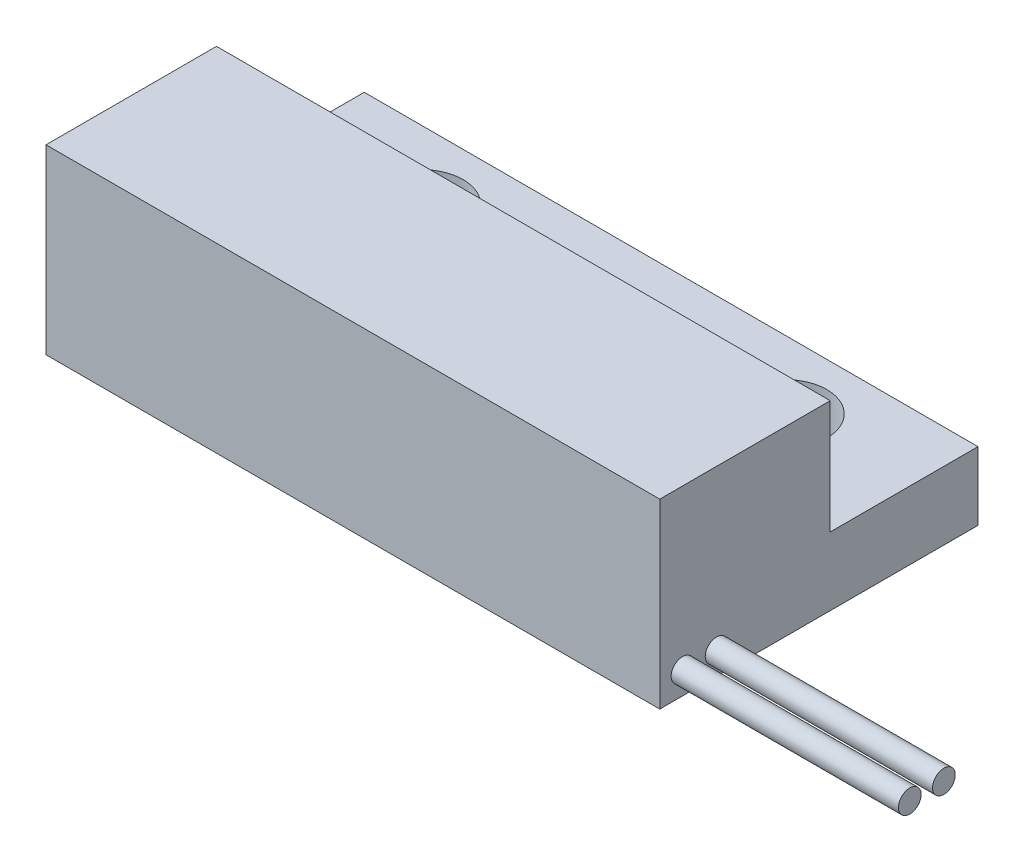
SolidWorks part; units mm, degrees
ref_plane "Alzado" through (0, 0, 0) normal (0, 0, 1) x (1, 0, 0)
ref_plane "Planta" through (0, 0, 0) normal (0, 1, 0) x (1, 0, 0)
ref_plane "Vista lateral" through (0, 0, 0) normal (1, 0, 0) x (0, 0, -1)
sketch "Croquis1" plane through (0, 0, 0) normal (0, 1, 0) x (1, 0, 0)
  line L0 (-13.5, 0) -> (-13.5, -3) construction
  line L1 (0, 0) -> (-27, 0)
  line L2 (0, 0) -> (0, -14)
  line L3 (0, -14) -> (-27, -14)
  line L4 (-27, 0) -> (-27, -14)
  line L5 (-13.5, -3) -> (-21.5, -3) construction
  line L6 (-21.5, -3) -> (-21.5, -14) construction
  line L7 (-21.5, -3) -> (-27, -3) construction
  circle A0 centre (-21.5, -3) radius 1.85
  circle A1 centre (-5.5, -3) radius 1.85
  dimension "D3" = 3.7
  dimension "D1" = 14
  dimension "D2" = 27
  dimension "D4" = 8
  dimension "D5" = 3
extrude "Saliente-Extruir1" add sketch "Croquis1" along normal blind 8
sketch "Croquis2" plane through (0, 8, 0) normal (0, 1, 0) x (1, 0, 0)
  line L0 (0, -14) -> (0, 0) construction
  line L1 (-27, 0) -> (0, 0)
  line L2 (-27, 0) -> (-27, -6.5)
  line L3 (-27, -6.5) -> (0, -6.5)
  line L4 (0, 0) -> (0, -6.5)
  line L5 (-27, -6.5) -> (-27, -14) construction
  dimension "D1" = 7.5
extrude "Cortar-Extruir1" cut sketch "Croquis2" against normal blind 5
sketch "Croquis3" plane through (0, 0, 0) normal (1, 0, 0) x (0, 0, -1)
  line L0 (-13, 1) -> (-11.5, 1) construction
  line L1 (-12.25, 1) -> (-12.25, 1.6216) construction
  line L2 (-14, 0) -> (0, 0) construction
  line L3 (-14, 8) -> (-14, 0) construction
  circle A0 centre (-13, 1) radius 0.5
  circle A1 centre (-11.5, 1) radius 0.5
  dimension "D4" = 1
  dimension "D1" = 1
  dimension "D2" = 1
  dimension "D3" = 1.5
extrude "Saliente-Extruir2" add sketch "Croquis3" along normal blind 10
